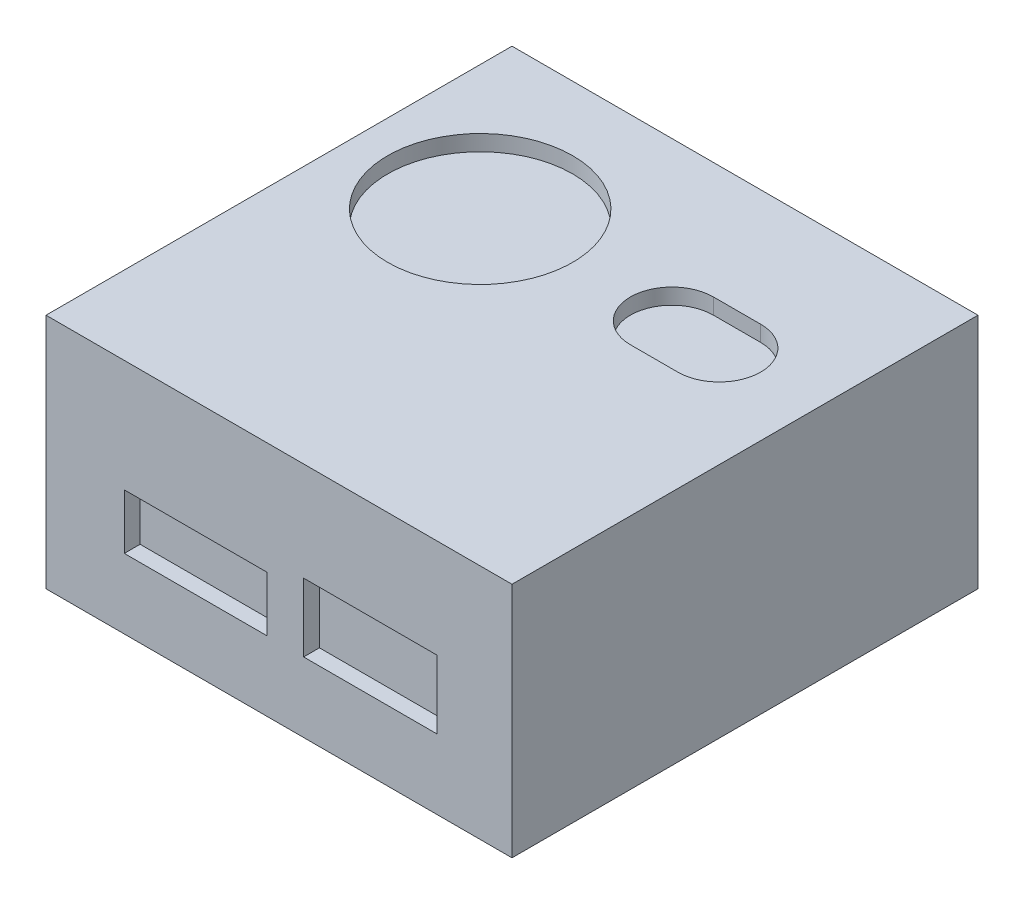
SolidWorks part; units mm, degrees
ref_plane "前视基准面" through (0, 0, 0) normal (0, 0, 1) x (1, 0, 0)
ref_plane "上视基准面" through (0, 0, 0) normal (0, 1, 0) x (1, 0, 0)
ref_plane "右视基准面" through (0, 0, 0) normal (1, 0, 0) x (0, 0, -1)
sketch "草图1" plane through (0, 0, 0) normal (0, 1, 0) x (1, 0, 0)
  line L1 (-14.75, 14.75) -> (14.75, 14.75)
  line L2 (-14.75, 14.75) -> (-14.75, -14.75)
  line L3 (-14.75, -14.75) -> (14.75, -14.75)
  line L4 (14.75, 14.75) -> (14.75, -14.75)
  line L5 (0, -14.75) -> (0, 14.75) construction
  line L6 (-14.75, 0) -> (14.75, 0) construction
  point P0 (0, 0)
  dimension "D1" = 29.5
  dimension "D2" = 29.5
extrude "凸台-拉伸1" add sketch "草图1" along normal blind 15
sketch "草图2" plane through (0, 15, 0) normal (0, 1, 0) x (1, 0, 0)
  line L0 (-342.0492, 522.1804) -> (369.9508, 522.1804) construction
sketch "草图3" plane through (0, 0, 14.75) normal (0, 0, 1) x (1, 0, 0)
  line L0 (76.291, 141.812) -> (440.291, 141.812) construction
sketch "草图4" plane through (0, 15, 0) normal (0, 1, 0) x (1, 0, 0)
  line L0 (5.3712, 4.7527) -> (8.3669, 4.7527) construction
  line L1 (5.3712, 7.3777) -> (8.3669, 7.3777)
  line L2 (5.3712, 2.1277) -> (8.3669, 2.1277)
  circle A0 centre (-6.8287, 4.8143) radius 5.8544
  arc A1 (5.3712, 7.3777) -> (5.3712, 2.1277) centre (5.3712, 4.7527) ccw
  arc A2 (8.3669, 2.1277) -> (8.3669, 7.3777) centre (8.3669, 4.7527) ccw
  point P4 (6.869, 4.7527)
extrude "切除-拉伸1" cut sketch "草图4" against normal blind 1
sketch "草图5" plane through (0, 0, 14.75) normal (0, 0, 1) x (1, 0, 0)
  line L1 (1.559, 4.4186) -> (9.9972, 4.4186)
  line L2 (1.559, 4.4186) -> (1.559, 8.7396)
  line L3 (1.559, 8.7396) -> (9.9972, 8.7396)
  line L4 (9.9972, 4.4186) -> (9.9972, 8.7396)
  line L5 (-9.7938, 4.4186) -> (-0.7442, 4.4186)
  line L6 (-9.7938, 4.4186) -> (-9.7938, 7.904)
  line L7 (-9.7938, 7.904) -> (-0.7442, 7.904)
  line L8 (-0.7442, 4.4186) -> (-0.7442, 7.904)
extrude "切除-拉伸2" cut sketch "草图5" against normal blind 1
equation "\"m\"= 2"
